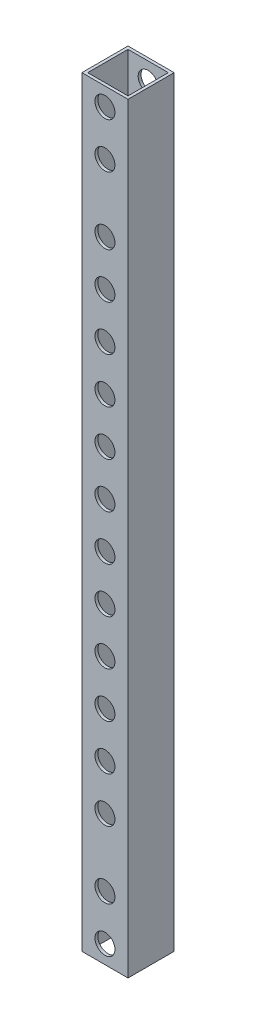
SolidWorks part; units mm, degrees
material "1060 Alloy"
ref_plane "Front Plane" through (0, 0, 0) normal (0, 0, 1) x (1, 0, 0)
ref_plane "Top Plane" through (0, 0, 0) normal (0, 1, 0) x (1, 0, 0)
ref_plane "Right Plane" through (0, 0, 0) normal (1, 0, 0) x (0, 0, -1)
sketch "Sketch1" plane through (0, 0, 0) normal (0, 1, 0) x (1, 0, 0)
  line L1 (-12.7, -12.7) -> (12.7, -12.7)
  line L2 (-12.7, -12.7) -> (-12.7, 12.7)
  line L3 (-12.7, 12.7) -> (12.7, 12.7)
  line L4 (12.7, -12.7) -> (12.7, 12.7)
  line L5 (-12.7, -12.7) -> (12.7, 12.7) construction
  line L6 (-12.7, 12.7) -> (12.7, -12.7) construction
  point P0 (0, 0)
  dimension "D1" = 25.4
extrude "Extrude-Thin1" add sketch "Sketch1" along normal blind 419.1 thin thin type one direction reverse wall 1.5875
sketch "Sketch2" plane through (0, 0, -12.7) normal (0, 0, -1) x (-1, 0, 0)
  line L0 (0, 419.1) -> (0, 0) construction
  line L1 (-12.7, 419.1) -> (12.7, 419.1) construction
  line L2 (-12.7, 0) -> (12.7, 0) construction
  line L3 (12.7, 209.55) -> (-12.7, 209.55) construction
  line L4 (12.7, 419.1) -> (12.7, 0) construction
  line L5 (-12.7, 419.1) -> (-12.7, 0) construction
  point P6 (0, 409.1)
  point P7 (0, 384.1)
  point P14 (0, 35)
  point P15 (0, 10)
  dimension "D1" = 10
  dimension "D2" = 25
hole_wizard "M10 Clearance Hole1" positions "Sketch3" profile "Sketch4" hole size "M10" standard "ANSI Metric" end condition through all
sketch "Sketch3" plane through (0, 0, -12.7) normal (0, 0, -1) x (-1, 0, 0)
  point P0 (0, 409.1)
  point P3 (0, 384.1)
  point P6 (0, 35)
  point P9 (0, 10)
sketch "Sketch4" plane through (0, 409.1, -12.7) normal (1, 0, 0) x (0, 1, 0)
  line L0 (0, 0) -> (0, 25.4)
  line L1 (0, 25.4) -> (5.5, 25.4)
  line L2 (5.5, 25.4) -> (5.5, 0.025)
  line L3 (5.5, 0.025) -> (5.525, 0)
  line L5 (5.525, 0) -> (0, 0)
  line L6 (-5.5, 0.025) -> (-5.525, 0) construction
  line L11 (0, -6.35) -> (0, 107.95) construction
  dimension "Thru Hole Dia." = 11
  dimension "Thru Hole Depth" = 25.4
  dimension "Near C'Sink Dia." = 11.05
  dimension "Near C'Sink Angle" = 90
sketch "Sketch5" plane through (0, 0, 12.7) normal (0, 0, 1) x (1, 0, 0)
  line L0 (0, 0) -> (0, 419.1) construction
  line L1 (-12.7, 0) -> (12.7, 0) construction
  line L2 (-12.7, 419.1) -> (12.7, 419.1) construction
  point P6 (0, 395.1442)
pattern_linear "LPattern1" [suppressed] count 8 spacing 50
sketch "Sketch6" plane through (0, 0, -12.7) normal (0, 0, -1) x (-1, 0, 0)
  line L0 (12.7, 209.55) -> (-12.7, 209.55) construction
  line L1 (0, 419.1) -> (0, 0) construction
  point P0 (0, 222.05)
  point P1 (0, 197.05)
  dimension "D1" = 12.5
  dimension "D2" = 12.5
hole_wizard "M10 Clearance Hole2" positions "Sketch7" profile "Sketch8" hole size "M10" standard "ANSI Metric" end condition through all
sketch "Sketch7" plane through (0, 0, -12.7) normal (0, 0, -1) x (-1, 0, 0)
  point P0 (0, 197.05)
  point P3 (0, 222.05)
sketch "Sketch8" plane through (0, 197.05, -12.7) normal (1, 0, 0) x (0, 1, 0)
  line L0 (0, 0) -> (0, 25.4)
  line L1 (0, 25.4) -> (5.5, 25.4)
  line L2 (5.5, 25.4) -> (5.5, 0.025)
  line L3 (5.5, 0.025) -> (5.525, 0)
  line L5 (5.525, 0) -> (0, 0)
  line L6 (-5.5, 0.025) -> (-5.525, 0) construction
  line L11 (0, -6.35) -> (0, 107.95) construction
  dimension "Thru Hole Dia." = 11
  dimension "Thru Hole Depth" = 25.4
  dimension "Near C'Sink Dia." = 11.05
  dimension "Near C'Sink Angle" = 90
pattern_linear "LPattern2" count 6 spacing 25 along (0, 1, 0) count 6 spacing 25 along (0, -1, 0) of "M10 Clearance Hole2"
